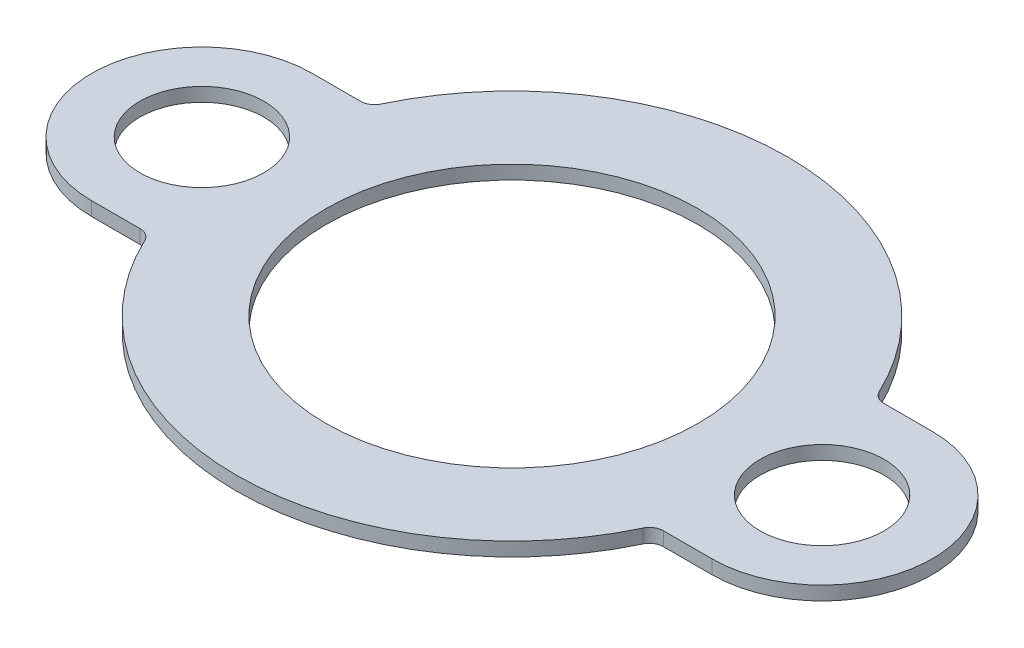
SolidWorks part; units mm, degrees
material "橡膠"
ref_plane "前基準面" through (0, 0, 0) normal (0, 0, 1) x (1, 0, 0)
ref_plane "上基準面" through (0, 0, 0) normal (0, 1, 0) x (1, 0, 0)
ref_plane "右基準面" through (0, 0, 0) normal (1, 0, 0) x (0, 0, -1)
sketch "草圖1" plane through (0, 0, 0) normal (0, 1, 0) x (1, 0, 0)
  line L0 (0, 0) -> (35.5012, 0) construction
  line L1 (0, 0) -> (0, 25.4318) construction
  line L2 (18.9737, 8) -> (22.5, 8)
  line L3 (22.5, -8) -> (18.9737, -8)
  line L4 (-22.5, -8) -> (-18.9737, -8)
  line L5 (-18.9737, 8) -> (-22.5, 8)
  circle A0 centre (0, 0) radius 13.5
  arc A1 (18.0702, 8.5714) -> (-18.0702, 8.5714) centre (0, 0) ccw
  arc A2 (22.5, 8) -> (22.5, -8) centre (22.5, 0) cw
  arc A3 (-22.5, 8) -> (-22.5, -8) centre (-22.5, 0) ccw
  arc A4 (-18.0702, -8.5714) -> (18.0702, -8.5714) centre (0, 0) ccw
  arc A5 (18.9737, 8) -> (18.0702, 8.5714) centre (18.9737, 9) cw
  arc A6 (18.9737, -8) -> (18.0702, -8.5714) centre (18.9737, -9) ccw
  arc A7 (-18.9737, -8) -> (-18.0702, -8.5714) centre (-18.9737, -9) cw
  arc A8 (-18.9737, 8) -> (-18.0702, 8.5714) centre (-18.9737, 9) ccw
  circle A9 centre (22.5, 0) radius 4.5
  circle A10 centre (-22.5, 0) radius 4.5
  point P17 (18.3303, 8)
  point P20 (18.3303, -8)
  point P23 (-18.3303, -8)
  point P26 (-18.3303, 8)
  dimension "D1" = 20
  dimension "D2" = 8
  dimension "D3" = 27
  dimension "D4" = 45
  dimension "D5" = 1
  dimension "D6" = 9
extrude "伸長1" add sketch "草圖1" along normal blind 1
